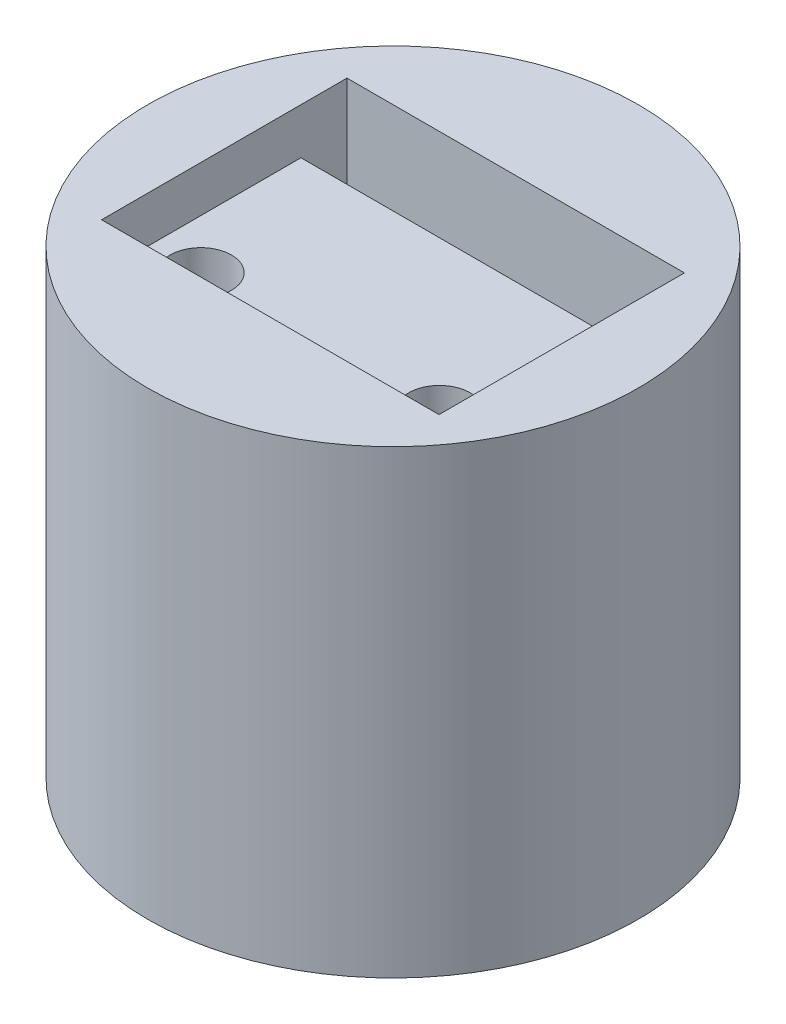
SolidWorks part; units mm, degrees
ref_plane "Front Plane" through (0, 0, 0) normal (0, 0, 1) x (1, 0, 0)
ref_plane "Top Plane" through (0, 0, 0) normal (0, 1, 0) x (1, 0, 0)
ref_plane "Right Plane" through (0, 0, 0) normal (1, 0, 0) x (0, 0, -1)
sketch "Sketch1" plane through (0, 0, 0) normal (0, 1, 0) x (1, 0, 0)
  circle A0 centre (0, 0) radius 16
  dimension "D1" = 32
extrude "Boss-Extrude1" add sketch "Sketch1" along normal blind 30
sketch "Sketch2" plane through (0, 30, 0) normal (0, 1, 0) x (1, 0, 0)
  line L1 (11, -8) -> (-11, -8)
  line L2 (11, -8) -> (11, 8)
  line L3 (11, 8) -> (-11, 8)
  line L4 (-11, -8) -> (-11, 8)
  line L5 (11, -8) -> (-11, 8) construction
  line L6 (11, 8) -> (-11, -8) construction
  point P0 (0, 0)
  dimension "D1" = 22
  dimension "D2" = 16
extrude "Cut-Extrude1" cut sketch "Sketch2" against normal blind 3
sketch "Sketch3" plane through (0, 27, 0) normal (0, 1, 0) x (1, 0, 0)
  line L0 (-11, 8) -> (-11, -8) construction
  circle A0 centre (-7.78, -4.7527) radius 1.6 construction
  circle A1 centre (7.78, -4.7527) radius 1.6 construction
  circle A2 centre (-7.78, -4.7527) radius 2
  circle A3 centre (7.78, -4.7527) radius 2
  dimension "D1" = 3.2
  dimension "D2" = 3.2
  dimension "D3" = 15.56
  dimension "D4" = 3.22
  dimension "D5" = 4
  dimension "D6" = 4
extrude "Cut-Extrude2" cut sketch "Sketch3" against normal blind 6.7
sketch "Sketch4" plane through (0, 27, 0) normal (0, 1, 0) x (1, 0, 0)
  line L0 (11, -8) -> (11, 8) construction
  line L1 (-11, 8) -> (11, 8)
  line L2 (-11, 8) -> (-11, 5)
  line L3 (-11, 5) -> (11, 5)
  line L4 (11, 8) -> (11, 5)
  dimension "D1" = 3
extrude "Cut-Extrude3" cut sketch "Sketch4" against normal blind 8.76
